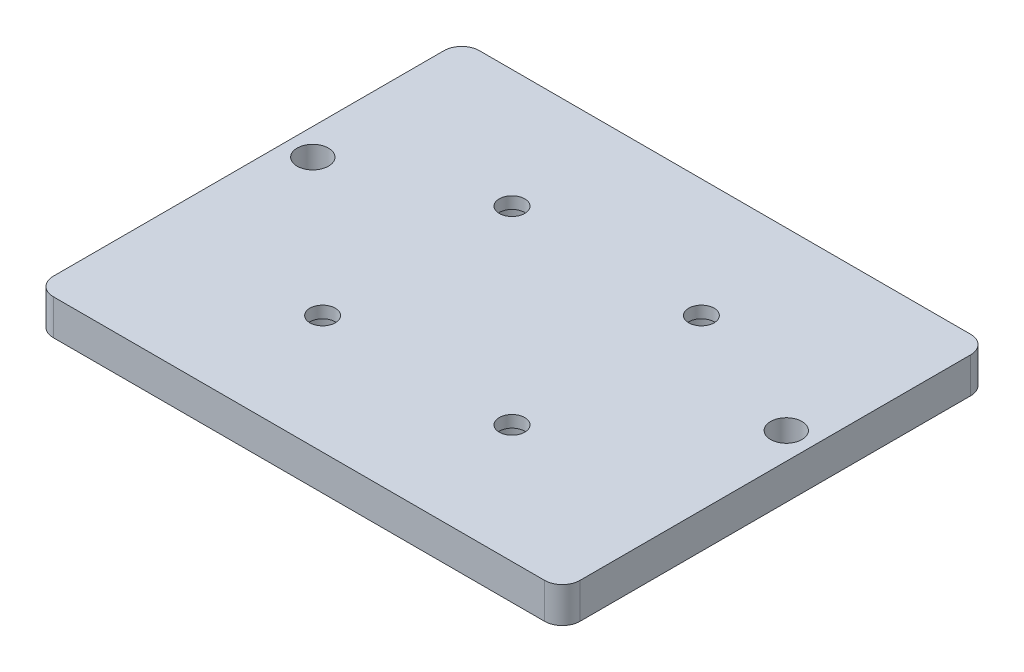
SolidWorks part; units mm, degrees
ref_plane "Front Plane" through (0, 0, 0) normal (0, 0, 1) x (1, 0, 0)
ref_plane "Top Plane" through (0, 0, 0) normal (0, 1, 0) x (1, 0, 0)
ref_plane "Right Plane" through (0, 0, 0) normal (1, 0, 0) x (0, 0, -1)
sketch "Sketch1" plane through (0, 0, 0) normal (0, 1, 0) x (1, 0, 0)
  line L0 (-40, 6.3443) -> (40, 6.3443) construction
  line L2 (16, -16) -> (-16, -16)
  line L3 (16, -16) -> (16, 16)
  line L4 (16, 16) -> (-16, 16)
  line L5 (-16, -16) -> (-16, 16)
  line L6 (16, -16) -> (-16, 16) construction
  line L7 (16, 16) -> (-16, -16) construction
  circle A0 centre (0, 0) radius 36
  circle A1 centre (-40, 6.3443) radius 4.5
  circle A2 centre (40, 6.3443) radius 4.5
  point P5 (0, 6.3443)
  dimension "D1" = 72
  dimension "D3" = 9
  dimension "D2" = 80
  dimension "D4" = 32
sketch "Sketch2" plane through (0, 0, 0) normal (0, 1, 0) x (1, 0, 0)
  line L1 (-44.5, 36) -> (44.5, 36)
  line L2 (-44.5, 36) -> (-44.5, -36)
  line L3 (-44.5, -36) -> (44.5, -36)
  line L4 (44.5, 36) -> (44.5, -36)
  circle A0 centre (0, 0) radius 36 construction
  circle A1 centre (-40, 6.3443) radius 4.5 construction
  point P4 (0, 36)
extrude "Boss-Extrude1" add sketch "Sketch2" along normal blind 6
hole_wizard "CBORE for M4 SHCS1" positions "Sketch3" profile "Sketch4" counterbore size "M4" standard "ANSI Metric" end condition up to next
sketch "Sketch3" plane through (0, 0, 0) normal (0, -1, 0) x (-1, 0, 0)
  point P0 (-16, -16)
  point P3 (-16, 16)
  point P6 (16, 16)
  point P9 (16, -16)
sketch "Sketch4" plane through (16, 0, 16) normal (1, 0, 0) x (0, 0, -1)
  line L0 (0, 0) -> (0, 6)
  line L1 (0, 6) -> (2.15, 6)
  line L3 (2.15, 6) -> (2.15, 4)
  line L4 (2.15, 4) -> (4, 4)
  line L5 (4, 4) -> (4, 0)
  line L7 (4, 0) -> (0, 0)
  line L11 (0, -6.35) -> (0, 107.95) construction
  dimension "Thru Hole Dia." = 4.3
  dimension "Thru Hole Depth" = 6
  dimension "C'Bore Dia." = 8
  dimension "C'Bore Depth" = 4
hole_wizard "M5 Clearance Hole1" positions "Sketch5" profile "Sketch6" hole size "M5" standard "ANSI Metric" end condition up to next
sketch "Sketch5" plane through (0, 6, 0) normal (0, 1, 0) x (1, 0, 0)
  point P0 (-40, 6.3443)
  point P3 (40, 6.3443)
sketch "Sketch6" plane through (-40, 6, -6.3443) normal (1, 0, 0) x (0, 0, 1)
  line L0 (0, 0) -> (0, 6)
  line L1 (0, 6) -> (2.65, 6)
  line L2 (2.65, 6) -> (2.65, 0)
  line L5 (2.65, 0) -> (0, 0)
  line L11 (0, -6.35) -> (0, 107.95) construction
  dimension "Thru Hole Dia." = 5.3
  dimension "Thru Hole Depth" = 6
fillet "Fillet1" radius 3 4 edges at (-44.5, 3, -36) (44.5, 3, -36) (44.5, 3, 36) (-44.5, 3, 36)
